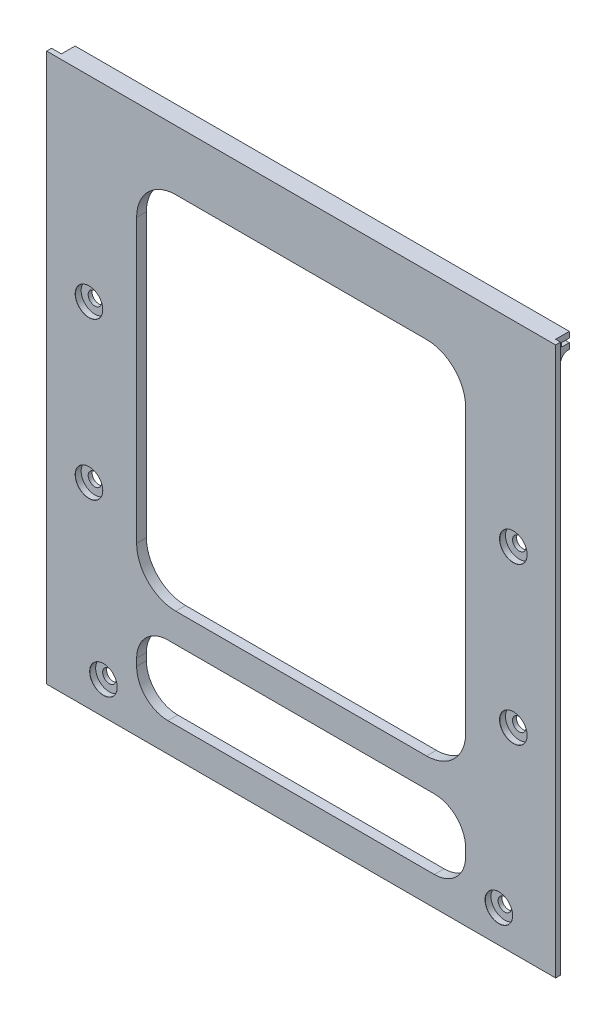
SolidWorks part; units mm, degrees
ref_plane "Plano frontal" through (0, 0, 0) normal (0, 0, 1) x (1, 0, 0)
ref_plane "Plano superior" through (0, 0, 0) normal (0, 1, 0) x (1, 0, 0)
ref_plane "Plano direito" through (0, 0, 0) normal (1, 0, 0) x (0, 0, -1)
other "Centro da massa"
sketch "Esboço1" plane through (0, 0, 0) normal (0, 0, 1) x (1, 0, 0)
  line L1 (-64.4893, 40.9259) -> (65.5107, 40.9259)
  line L2 (-64.4893, 40.9259) -> (-64.4893, -99.1241)
  line L3 (-64.4893, -99.1241) -> (65.5107, -99.1241)
  line L4 (65.5107, 40.9259) -> (65.5107, -99.1241)
  dimension "D1" = 130
  dimension "D2" = 140.05
extrude "Ressalto-extrusão1" add sketch "Esboço1" along normal blind 2.5
sketch "Esboço2" plane through (0, 0, 0) normal (0, 0, -1) x (-1, 0, 0)
  line L0 (64.4893, 40.9259) -> (64.4893, -99.1241) construction
  line L1 (-65.5107, 40.9259) -> (64.4893, 40.9259)
  line L2 (-65.5107, 40.9259) -> (-65.5107, 36.9259)
  line L3 (-65.5107, 36.9259) -> (64.4893, 36.9259)
  line L4 (64.4893, 40.9259) -> (64.4893, 36.9259)
  dimension "D1" = 4
extrude "Ressalto-extrusão2" add sketch "Esboço2" along normal blind 2.25
fillet "Filete1" radius 2 1 edges at (0.5107, 36.9259, 0)
sketch "Esboço3" plane through (0, 0, -2.25) normal (0, 0, -1) x (-1, 0, 0)
  line L0 (-65.5107, 40.9259) -> (-65.5107, 36.9259) construction
  line L1 (-65.5107, 39.4259) -> (64.4893, 39.4259)
  line L2 (-65.5107, 39.4259) -> (-65.5107, 38.4259)
  line L3 (-65.5107, 38.4259) -> (64.4893, 38.4259)
  line L4 (64.4893, 39.4259) -> (64.4893, 38.4259)
  line L5 (64.4893, 36.9259) -> (64.4893, 40.9259) construction
  line L6 (-65.5107, 40.9259) -> (-65.5107, 39.4259)
  line L7 (-65.5107, 38.4259) -> (-65.5107, 36.9259)
  line M7 (-65.5107, 40.9259) -> (-65.5107, 36.9259)
  line M9 (64.4893, 36.9259) -> (64.4893, 40.9259)
  dimension "D1" = 1
extrude "Corte-extrusão1" cut sketch "Esboço3" against normal blind 2 contours L3 L1 M7 M9
sketch "Esboço6" plane through (0, 0, -2.25) normal (0, 0, -1) x (-1, 0, 0)
  line L0 (64.4893, -99.1241) -> (-65.5107, -99.1241) construction
  line L1 (-65.5107, 40.9259) -> (-64.2607, 40.9259)
  line L2 (-65.5107, 40.9259) -> (-65.5107, -99.1241)
  line L3 (-65.5107, -99.1241) -> (-64.2607, -99.1241)
  line L4 (-64.2607, 40.9259) -> (-64.2607, -99.1241)
  line L5 (-0.5107, 40.9259) -> (-0.5107, -99.1241) construction
  line L6 (64.4893, 40.9259) -> (-65.5107, 40.9259) construction
  line L7 (64.4893, -99.1241) -> (63.2393, -99.1241)
  line L8 (63.2393, 40.9259) -> (63.2393, -99.1241)
  line L9 (64.4893, 40.9259) -> (63.2393, 40.9259)
  line L10 (64.4893, 40.9259) -> (64.4893, -99.1241)
  dimension "D1" = 1.25
extrude "Corte-extrusão2" cut sketch "Esboço6" against normal blind 3.5
sketch "Esboço8" plane through (0, 40.9259, 0) normal (0, 1, 0) x (1, 0, 0)
  line L1 (-63.2393, 2.25) -> (-61.9893, 2.25)
  line L2 (-63.2393, 2.25) -> (-63.2393, -1.25)
  line L3 (-63.2393, -1.25) -> (-61.9893, -1.25)
  line L4 (-61.9893, 2.25) -> (-61.9893, -1.25)
  dimension "D1" = 1.25
extrude "Corte-extrusão3" cut sketch "Esboço8" against normal blind 6.25
sketch "Esboço10" plane through (0, 0, 2.5) normal (0, 0, 1) x (1, 0, 0)
  line L0 (0.5107, 40.9259) -> (0.5107, -99.1241) construction
  line L1 (65.5107, 40.9259) -> (-64.4893, 40.9259) construction
  line L2 (-64.4893, -99.1241) -> (65.5107, -99.1241) construction
  line L3 (-53.6893, 40.9259) -> (-53.6893, -99.1241) construction
  line L4 (-64.4893, 40.9259) -> (-64.4893, -99.1241) construction
  line L5 (-64.4893, -9.1241) -> (0.5107, -9.1241) construction
  circle A0 centre (-53.6893, -9.1241) radius 1.5
  circle A1 centre (-53.6893, -49.1241) radius 1.5
  circle A2 centre (54.7107, -49.1241) radius 1.5
  circle A3 centre (54.7107, -9.1241) radius 1.5
  point P16 (-53.6893, -7.6241)
  point P17 (-53.6893, -50.6241)
  dimension "D2" = 3
  dimension "D4" = 43
  dimension "D1" = 10.8
  dimension "D3" = 50.05
hole_wizard "Rebaixo para parafuso com cabeça panela de M31" positions "Esboço11" profile "Esboço12" counterbore size "M3" standard "ISO" end condition through all
sketch "Esboço11" plane through (0, 0, 2.5) normal (0, 0, 1) x (1, 0, 0)
  point P0 (-53.6893, -9.1241)
  point P3 (-53.6893, -49.1241)
  point P6 (54.7107, -9.1241)
  point P9 (54.7107, -49.1241)
sketch "Esboço12" plane through (-53.6893, -9.1241, 2.5) normal (1, 0, 0) x (0, -1, 0)
  line L0 (0, 0) -> (0, 4.75)
  line L1 (0, 4.75) -> (1.7, 4.75)
  line L3 (1.7, 4.75) -> (1.7, 1.5)
  line L4 (3.5, 1.5) -> (1.7, 1.5)
  line L5 (3.5, 1.5) -> (3.5, 0.025)
  line L6 (3.5, 0.025) -> (3.525, 0)
  line L7 (3.525, 0) -> (0, 0)
  line L8 (-3.5, 0.025) -> (-3.525, 0) construction
  line L11 (0, -6.35) -> (0, 107.95) construction
  dimension "Thru Hole Dia." = 3.4
  dimension "Thru Hole Depth" = 4.75
  dimension "C'Bore Dia." = 7
  dimension "C'Bore Depth" = 1.5
  dimension "Near C'Sink Dia." = 7.05
  dimension "Near C'Sink Angle" = 90
sketch "Esboço13" plane through (0, 0, 2.5) normal (0, 0, 1) x (1, 0, 0)
  line L0 (0.5107, 40.9259) -> (0.5107, -99.1241) construction
  line L1 (32.536, -66.4862) -> (-31.5147, -66.4862)
  line L2 (42.536, -56.4862) -> (42.536, 15.6392)
  line L3 (32.536, 25.6392) -> (-31.5147, 25.6392)
  line L4 (-41.5147, -56.4862) -> (-41.5147, 15.6392)
  line L5 (42.536, -66.4862) -> (-41.5147, 25.6392) construction
  line L6 (42.536, 25.6392) -> (-41.5147, -66.4862) construction
  line L8 (34.536, -91.705) -> (-33.5147, -91.705)
  line L9 (42.536, -83.705) -> (42.536, -81.8806)
  line L10 (34.536, -73.8806) -> (-33.5147, -73.8806)
  line L11 (-41.5147, -83.705) -> (-41.5147, -81.8806)
  line L12 (42.536, -91.705) -> (-41.5147, -73.8806) construction
  line L13 (42.536, -73.8806) -> (-41.5147, -91.705) construction
  arc A0 (42.536, 15.6392) -> (32.536, 25.6392) centre (32.536, 15.6392) ccw
  arc A1 (32.536, -66.4862) -> (42.536, -56.4862) centre (32.536, -56.4862) ccw
  arc A2 (-31.5147, -66.4862) -> (-41.5147, -56.4862) centre (-31.5147, -56.4862) cw
  arc A3 (-31.5147, 25.6392) -> (-41.5147, 15.6392) centre (-31.5147, 15.6392) ccw
  arc A4 (34.536, -91.705) -> (42.536, -83.705) centre (34.536, -83.705) ccw
  arc A5 (42.536, -81.8806) -> (34.536, -73.8806) centre (34.536, -81.8806) ccw
  arc A6 (-33.5147, -91.705) -> (-41.5147, -83.705) centre (-33.5147, -83.705) cw
  arc A7 (-33.5147, -73.8806) -> (-41.5147, -81.8806) centre (-33.5147, -81.8806) ccw
  point P0 (0.5107, -20.4235)
  point P19 (0.5107, -82.7928)
  dimension "D1" = 10
  dimension "D2" = 8
extrude "Corte-extrusão5" cut sketch "Esboço13" against normal blind 8.25
sketch "Esboço14" plane through (0, 0, 2.5) normal (0, 0, 1) x (1, 0, 0)
  line L0 (-49.9893, -99.1241) -> (-49.9893, -75.15) construction
  line L1 (-64.4893, -99.1241) -> (65.5107, -99.1241) construction
  line L2 (-64.4893, 40.9259) -> (-64.4893, -99.1241) construction
  line L3 (0.5107, -99.1241) -> (0.5107, -90.8241) construction
  line L4 (0.5107, 40.9259) -> (0.5107, -99.1241) construction
  circle A0 centre (-49.9893, -90.8241) radius 3.7
  circle A1 centre (51.0107, -90.8241) radius 3.7
  point P8 (-49.9893, -87.1241)
  dimension "D1" = 14.5
  dimension "D2" = 8.3
hole_wizard "Rebaixo para parafuso com cabeça panela de M32" positions "Esboço15" profile "Esboço16" counterbore size "M3" standard "ISO" end condition through all
sketch "Esboço15" plane through (0, 0, 2.5) normal (0, 0, 1) x (1, 0, 0)
  point P0 (-49.9893, -90.8241)
  point P3 (51.0107, -90.8241)
sketch "Esboço16" plane through (-49.9893, -90.8241, 2.5) normal (1, 0, 0) x (0, -1, 0)
  line L0 (0, 0) -> (0, 4.75)
  line L1 (0, 4.75) -> (1.7, 4.75)
  line L3 (1.7, 4.75) -> (1.7, 1.5)
  line L4 (3.5, 1.5) -> (1.7, 1.5)
  line L5 (3.5, 1.5) -> (3.5, 0.025)
  line L6 (3.5, 0.025) -> (3.525, 0)
  line L7 (3.525, 0) -> (0, 0)
  line L8 (-3.5, 0.025) -> (-3.525, 0) construction
  line L11 (0, -6.35) -> (0, 107.95) construction
  dimension "Thru Hole Dia." = 3.4
  dimension "Thru Hole Depth" = 4.75
  dimension "C'Bore Dia." = 7
  dimension "C'Bore Depth" = 1.5
  dimension "Near C'Sink Dia." = 7.05
  dimension "Near C'Sink Angle" = 90
